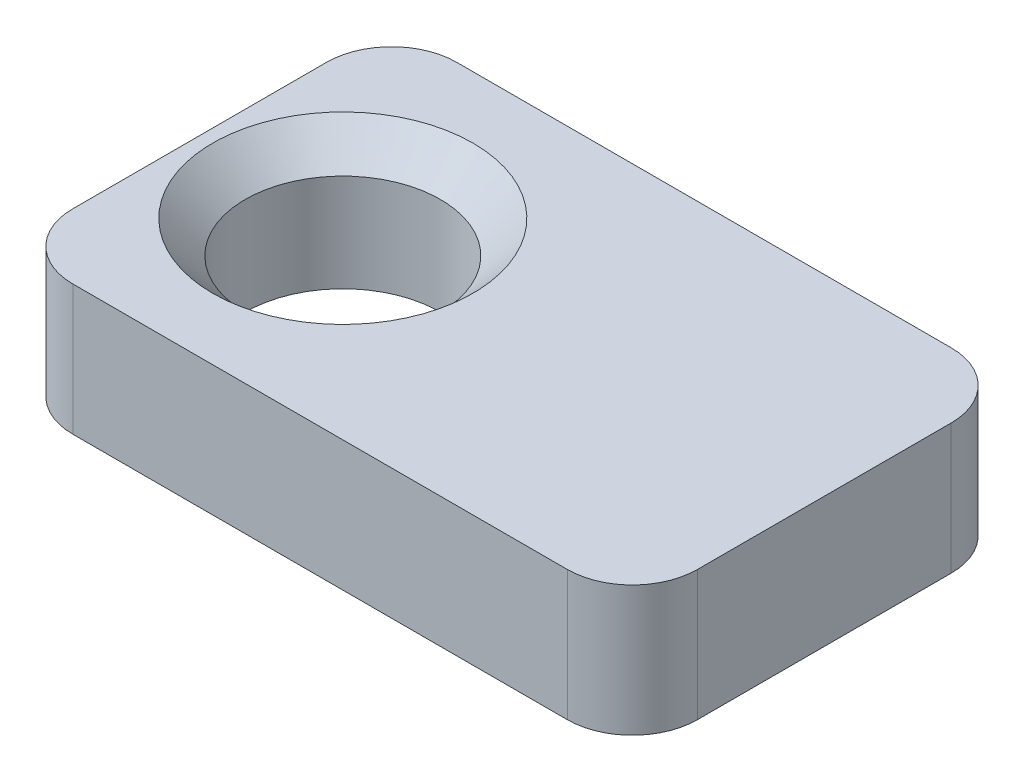
SolidWorks part; units mm, degrees
ref_plane "Front Plane" through (0, 0, 0) normal (0, 0, 1) x (1, 0, 0)
ref_plane "Top Plane" through (0, 0, 0) normal (0, 1, 0) x (1, 0, 0)
ref_plane "Right Plane" through (0, 0, 0) normal (1, 0, 0) x (0, 0, -1)
sketch "Sketch1" plane through (0, 0, 0) normal (0, 1, 0) x (1, 0, 0)
  line L1 (0, 0) -> (4.8, 0)
  line L2 (0, 0) -> (0, 2.95)
  line L3 (0, 2.95) -> (4.8, 2.95)
  line L4 (4.8, 0) -> (4.8, 2.95)
  dimension "D1" = 2.95
  dimension "D2" = 4.8
extrude "Boss-Extrude1" add sketch "Sketch1" along normal blind 1
sketch "Sketch2" plane through (0, 1, 0) normal (0, 1, 0) x (1, 0, 0)
  line L0 (4.8, 1.475) -> (0, 1.475) construction
  line L1 (4.8, 0) -> (4.8, 2.95) construction
  line L2 (0, 2.95) -> (0, 0) construction
  point P6 (1.1, 1.475)
  dimension "D1" = 1.1
hole_wizard "CSK for M2 Flat Head Machine Screw1" positions "3DSketch1" profile "Sketch4" countersink size "M2" standard "ANSI Metric" end condition through all
sketch3d "3DSketch1"
  point P0 (1.1, 1, -1.475)
sketch "Sketch4" plane through (1.1, 1, -1.475) normal (1, 0, 0) x (0, 0, 1)
  line L0 (0, 0) -> (0, 1)
  line L1 (0, 1) -> (0.75, 1)
  line L2 (0.75, 1) -> (0.75, 0.25)
  line L3 (0.75, 0.25) -> (1, 0)
  line L5 (1, 0) -> (0, 0)
  line L6 (-0.75, 0.25) -> (-1, 0) construction
  line L11 (0, -6.35) -> (0, 107.95) construction
  dimension "Thru Hole Dia." = 1.5
  dimension "Thru Hole Depth" = 1
  dimension "Near C'Sink Dia." = 2
  dimension "Near C'Sink Angle" = 90
fillet "Fillet1" radius 0.5 4 edges at (4.8, 0.5, 0) (4.8, 0.5, -2.95) (0, 0.5, -2.95) (0, 0.5, 0)
